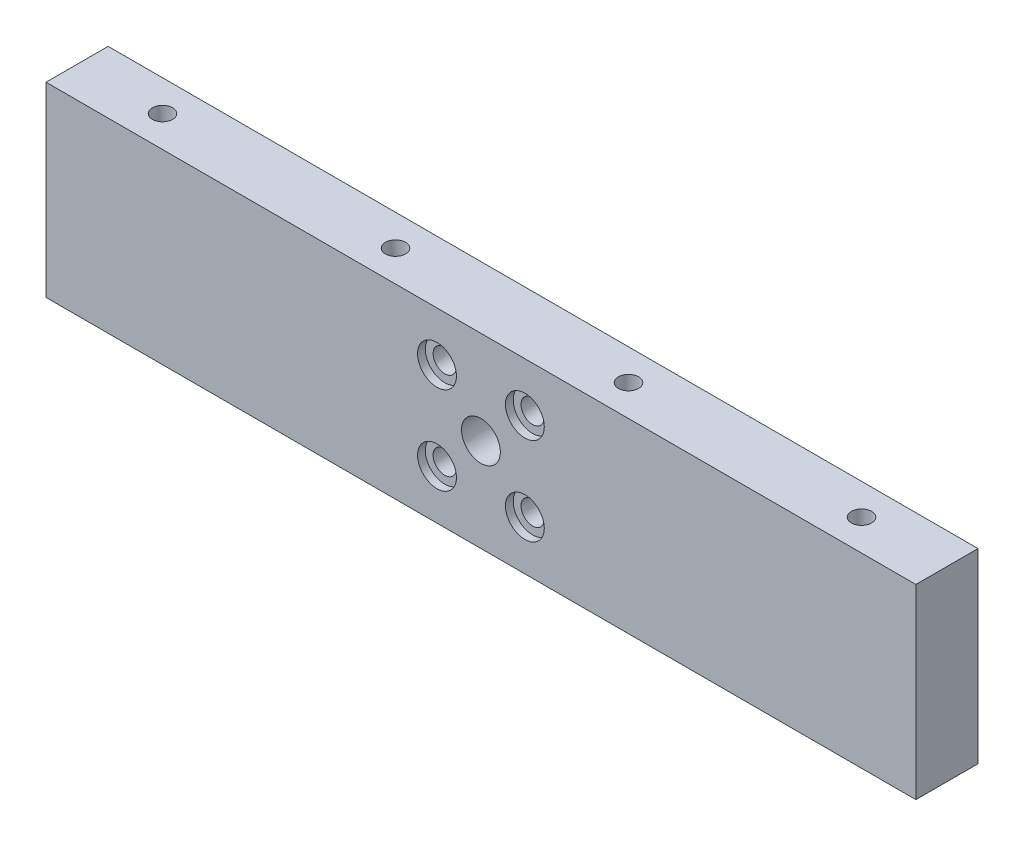
SolidWorks part; units mm, degrees
ref_plane "前视基准面" through (0, 0, 0) normal (0, 0, 1) x (1, 0, 0)
ref_plane "上视基准面" through (0, 0, 0) normal (0, 1, 0) x (1, 0, 0)
ref_plane "右视基准面" through (0, 0, 0) normal (1, 0, 0) x (0, 0, -1)
sketch "草图1" plane through (0, 0, 0) normal (0, 0, 1) x (1, 0, 0)
  line L1 (-56, -12) -> (56, -12)
  line L2 (-56, -12) -> (-56, 12)
  line L3 (-56, 12) -> (56, 12)
  line L4 (56, -12) -> (56, 12)
  line L5 (-56, -12) -> (56, 12) construction
  line L6 (-56, 12) -> (56, -12) construction
  point P0 (0, 0)
  dimension "D1" = 112
  dimension "D2" = 24
extrude "凸台-拉伸1" add sketch "草图1" along normal blind 8
sketch "草图2" plane through (0, 12, 0) normal (0, 1, 0) x (1, 0, 0)
  line L0 (-56, -4) -> (56, -4) construction
  line L1 (-56, -8) -> (-56, 0) construction
  line L2 (56, -8) -> (56, 0) construction
  line L3 (0, 0) -> (0, -8) construction
  line L4 (56, 0) -> (-56, 0) construction
  line L5 (56, -8) -> (-56, -8) construction
  circle A0 centre (-15, -4) radius 1.3
  circle A1 centre (-45, -4) radius 1.3
  circle A2 centre (45, -4) radius 1.3
  circle A3 centre (15, -4) radius 1.3
  dimension "D1" = 2.6
  dimension "D2" = 2.6
  dimension "D3" = 15
  dimension "D4" = 30
extrude "切除-拉伸1" cut sketch "草图2" against normal blind 30
sketch "草图3" plane through (0, 0, 0) normal (0, 0, -1) x (-1, 0, 0)
  line L0 (-5.6569, -5.6569) -> (0, 0) construction
  line L1 (-5.6569, 5.6569) -> (0, 0) construction
  line L2 (5.6569, 5.6569) -> (0, 0) construction
  line L3 (5.6569, -5.6569) -> (0, 0) construction
  circle A0 centre (0, 0) radius 2.5
  circle A1 centre (-5.6569, -5.6569) radius 1.5
  circle A2 centre (0, 0) radius 8 construction
  circle A3 centre (-5.6569, 5.6569) radius 1.5
  circle A4 centre (5.6569, 5.6569) radius 1.5
  circle A5 centre (5.6569, -5.6569) radius 1.5
  point P14 (0, 0)
  point P16 (0, 0)
  point P18 (0, 0)
  dimension "D1" = 5
  dimension "D2" = 3
  dimension "D3" = 16
  dimension "D4" = 5.6569
extrude "切除-拉伸2" cut sketch "草图3" against normal through all
sketch "草图4" plane through (0, 0, 0) normal (0, 0, -1) x (-1, 0, 0)
  circle A0 centre (0, 0) radius 11.25
  dimension "D1" = 22.5
sketch "草图5" plane through (0, 0, 8) normal (0, 0, 1) x (1, 0, 0)
  circle A0 centre (-5.6569, -5.6569) radius 2.5
  circle A2 centre (5.6569, -5.6569) radius 2.5
  circle A3 centre (5.6569, 5.6569) radius 2.5
  circle A4 centre (-5.6569, 5.6569) radius 2.5
  circle A5 centre (5.6569, -5.6569) radius 1.5 construction
  dimension "D1" = 5
  dimension "D2" = 5
  dimension "D3" = 5
  dimension "D4" = 5
extrude "切除-拉伸4" cut sketch "草图5" against normal blind 1
